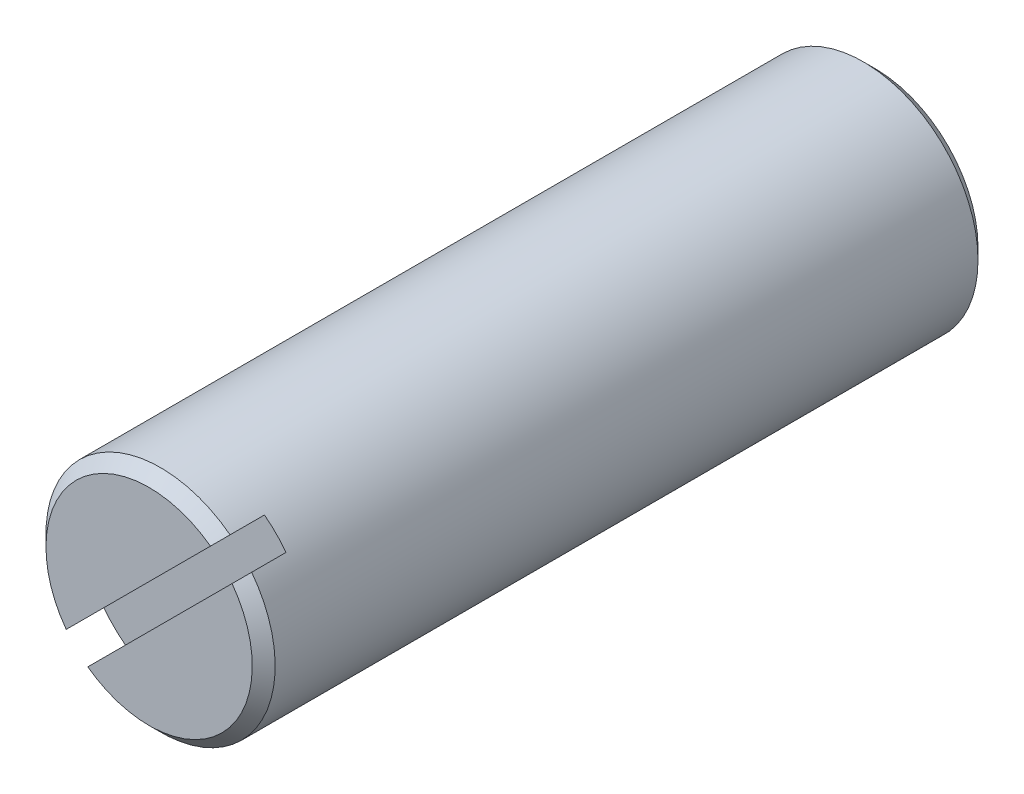
SolidWorks part; units mm, degrees
ref_plane "Face" through (0, 0, 0) normal (0, 0, 1) x (1, 0, 0)
ref_plane "Dessus" through (0, 0, 0) normal (0, 1, 0) x (1, 0, 0)
ref_plane "Droite" through (0, 0, 0) normal (1, 0, 0) x (0, 0, -1)
sketch "Esquisse1" plane through (0, 0, 0) normal (0, 0, 1) x (1, 0, 0)
  circle A0 centre (0, 0) radius 15
  dimension "D1" = 30
extrude "Base-Extrusion" add sketch "Esquisse1" along normal blind 95
chamfer "Chanfrein1" distance 1.5 angle 45 2 edges at (15, 0, 0) (15, 0, 95)
ref_plane "Plan3" through (15, 0, 0) normal (1, 0, 0) x (0, 0, -1)
sketch "Esquisse2" plane through (15, 0, 0) normal (1, 0, 0) x (0, 0, -1)
  line L0 (0, -13.5) -> (0, 13.5) construction
  line L1 (-20, -13) -> (-75, -13)
  line L2 (-20, -13) -> (-20, -18)
  line L3 (-20, -18) -> (-75, -18)
  line L4 (-75, -13) -> (-75, -18)
  line L5 (0, -13.5) -> (0, 13.5) construction
  line L6 (-1.5, 15) -> (-93.5, 15) construction
  line L7 (-1.5, 15) -> (-93.5, 15) construction
  dimension "D1" = 55
  dimension "D2" = 20
  dimension "D3" = 28
  dimension "D4" = 5
extrude "Méplat" cut sketch "Esquisse2" against normal through all
sketch "Esquisse3" plane through (0, 0, 95) normal (0, 0, 1) x (1, 0, 0)
  line L0 (-11.8293, -11.8293) -> (11.8293, 11.8293) construction
  line L1 (-21.445, 0) -> (21.445, 0) construction
  line L2 (-10.9602, -13.7886) -> (13.7886, 10.9602)
  line L3 (13.7886, 10.9602) -> (10.9602, 13.7886)
  line L4 (10.9602, 13.7886) -> (-13.7886, -10.9602)
  line L5 (-13.7886, -10.9602) -> (-10.9602, -13.7886)
  dimension "D1" = 45
  dimension "D2" = 4
  dimension "D3" = 35
  dimension "D4" = 17.5
extrude "Rainure" cut sketch "Esquisse3" against normal blind 6
ref_plane "Plan4" through (0, 0, 47.5) normal (0, 0, 1) x (1, 0, 0)
